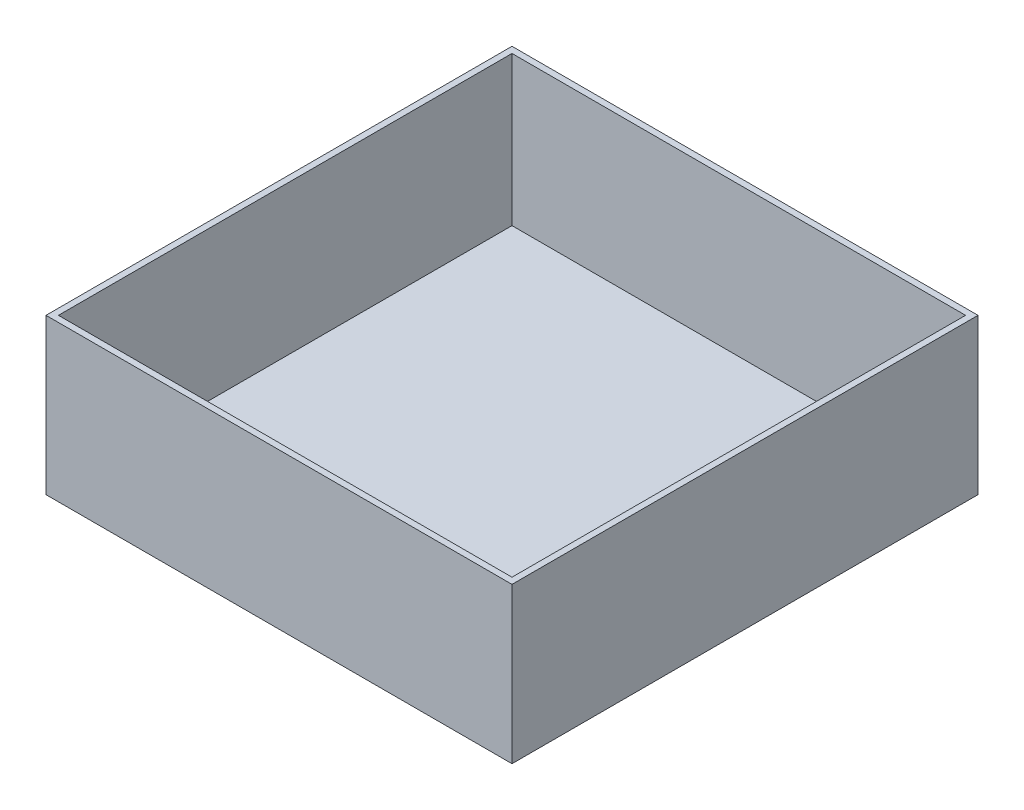
SolidWorks part; units mm, degrees
ref_plane "Front Plane" through (0, 0, 0) normal (0, 0, 1) x (1, 0, 0)
ref_plane "Top Plane" through (0, 0, 0) normal (0, 1, 0) x (1, 0, 0)
ref_plane "Right Plane" through (0, 0, 0) normal (1, 0, 0) x (0, 0, -1)
sketch "Sketch1" plane through (0, 0, 0) normal (0, 1, 0) x (1, 0, 0)
  line L1 (-75, 75) -> (75, 75)
  line L2 (-75, 75) -> (-75, -75)
  line L3 (-75, -75) -> (75, -75)
  line L4 (75, 75) -> (75, -75)
  line L5 (-75, 75) -> (75, -75) construction
  line L6 (-75, -75) -> (75, 75) construction
  point P0 (0, 0)
  dimension "D1" = 150
  dimension "D2" = 150
extrude "Boss-Extrude1" add sketch "Sketch1" along normal blind 50
sketch "Sketch2" plane through (0, 0, 0) normal (0, 1, 0) x (1, 0, 0)
  line L1 (-73, 73) -> (73, 73)
  line L2 (-73, 73) -> (-73, -73)
  line L3 (-73, -73) -> (73, -73)
  line L4 (73, 73) -> (73, -73)
  line L5 (-73, 73) -> (73, -73) construction
  line L6 (-73, -73) -> (73, 73) construction
  point P0 (0, 0)
  dimension "D1" = 146
  dimension "D2" = 146
extrude "Cut-Extrude1" cut sketch "Sketch2" along normal up to surface (48 mm away) from offset 2 up to face at (0, 50, 0)
